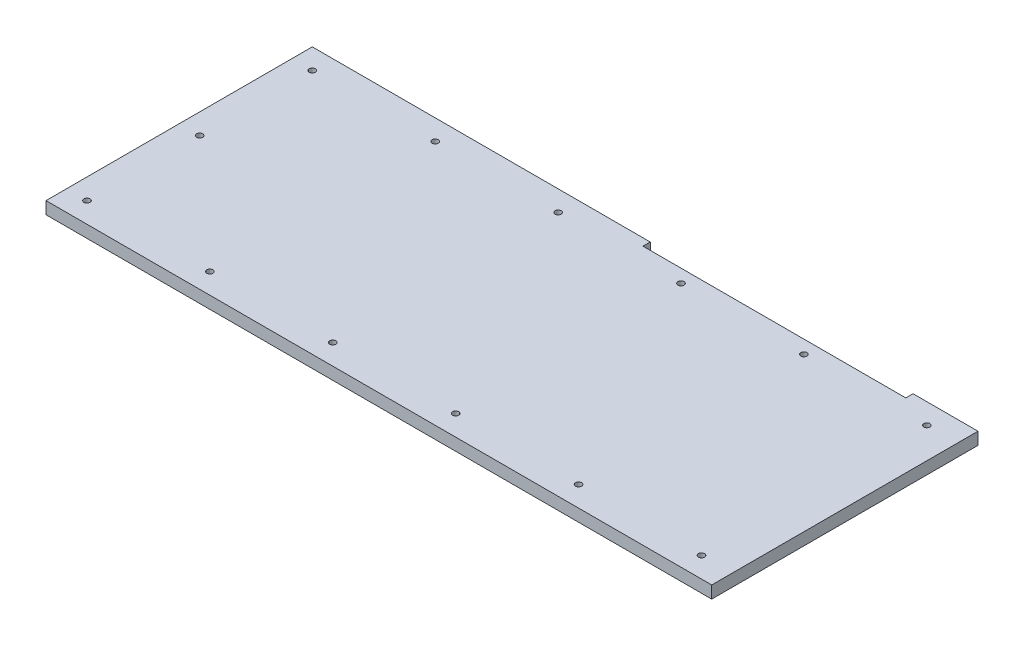
SolidWorks part; units mm, degrees
ref_plane "前视基准面" through (0, 0, 0) normal (0, 0, 1) x (1, 0, 0)
ref_plane "上视基准面" through (0, 0, 0) normal (0, 1, 0) x (1, 0, 0)
ref_plane "右视基准面" through (0, 0, 0) normal (1, 0, 0) x (0, 0, -1)
sketch "草图1" plane through (0, 0, 0) normal (0, 1, 0) x (1, 0, 0)
  line L0 (-162.5, -55) -> (162.5, -55) construction
  line L1 (-162.5, 65) -> (2.4978, 65)
  line L2 (-162.5, 65) -> (-162.5, -65)
  line L3 (-162.5, -65) -> (162.5, -65)
  line L4 (162.5, 65) -> (162.5, -65)
  line L5 (-162.5, 55) -> (162.5, 55) construction
  line L6 (-152.5, 65) -> (-152.5, -65) construction
  line L7 (130.7858, 65) -> (130.7858, 61.4546)
  line L8 (130.7858, 61.4546) -> (2.4978, 61.4546)
  line L9 (2.4978, 61.4546) -> (2.4978, 65)
  line L10 (130.7858, 65) -> (162.5, 65)
  circle A0 centre (-152.5, 55) radius 1.5
  circle A1 centre (-152.5, -55) radius 1.5
  circle A2 centre (-92.5, 55) radius 1.5
  circle A3 centre (-32.5, 55) radius 1.5
  circle A4 centre (27.5, 55) radius 1.5
  circle A5 centre (87.5, 55) radius 1.5
  circle A6 centre (147.5, 55) radius 1.5
  circle A7 centre (-92.5, -55) radius 1.5
  circle A8 centre (-32.5, -55) radius 1.5
  circle A9 centre (27.5, -55) radius 1.5
  circle A10 centre (87.5, -55) radius 1.5
  circle A11 centre (147.5, -55) radius 1.5
  circle A12 centre (-152.5, 0) radius 1.5
  dimension "D8" = 3
  dimension "D9" = 3
  dimension "D12" = 3
  dimension "D1" = 325
  dimension "D2" = 130
  dimension "D3" = 65
  dimension "D4" = 162.5
  dimension "D5" = 10
  dimension "D6" = 10
  dimension "D7" = 10
  dimension "D10" = 6
  dimension "D11" = 6
extrude "凸台-拉伸1" add sketch "草图1" along normal blind 6
